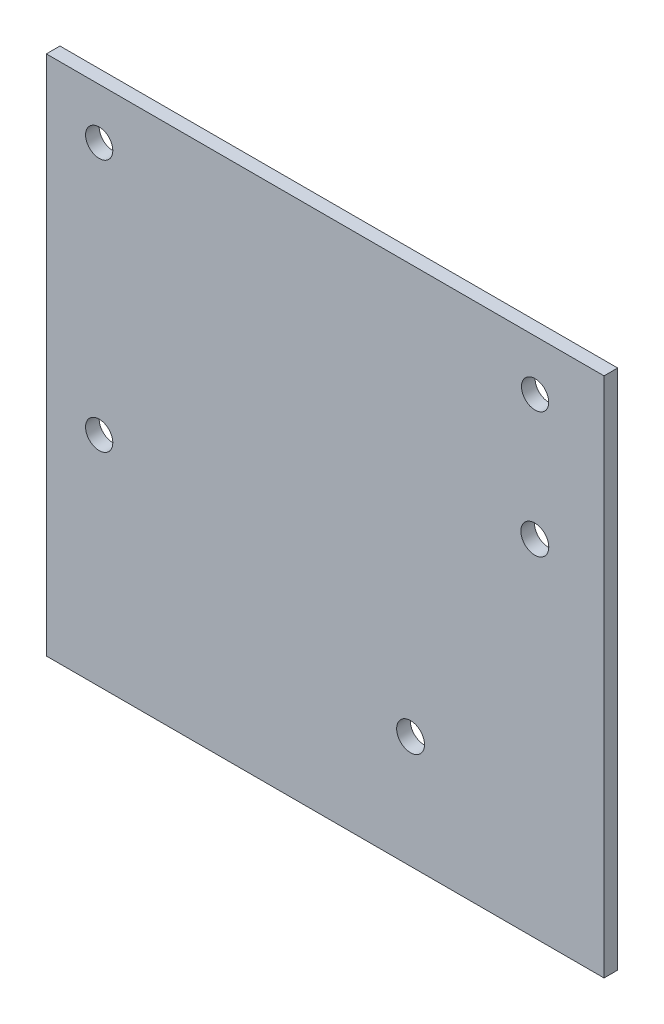
SolidWorks part; units mm, degrees
ref_plane "Front Plane" through (0, 0, 0) normal (0, 0, 1) x (1, 0, 0)
ref_plane "Top Plane" through (0, 0, 0) normal (0, 1, 0) x (1, 0, 0)
ref_plane "Right Plane" through (0, 0, 0) normal (1, 0, 0) x (0, 0, -1)
sketch "Sketch1" plane through (0, 0, 0) normal (0, 0, 1) x (1, 0, 0)
  line L0 (59.8766, 278.2835) -> (9.0766, 278.2835) construction
  line L1 (-37.716, 306.5959) -> (92.264, 306.5959)
  line L2 (-37.716, 306.5959) -> (-37.716, 185.0571)
  line L3 (-37.716, 185.0571) -> (92.264, 185.0571)
  line L4 (92.264, 306.5959) -> (92.264, 185.0571)
  line L5 (59.8766, 227.4835) -> (59.8766, 278.2835) construction
  line L6 (9.0766, 227.4835) -> (59.8766, 227.4835) construction
  circle A0 centre (-25.4, 235.8571) radius 3.175
  circle A1 centre (-25.4, 294.8214) radius 3.175
  circle A3 centre (76.2, 294.8214) radius 3.175
  circle A4 centre (76.1326, 265.5835) radius 3.2512
  circle A5 centre (47.1766, 211.2275) radius 3.2512
  dimension "D2" = 6.35
  dimension "D3" = 6.35
  dimension "D6" = 6.35
  dimension "D9" = 6.5024
  dimension "D12" = 6.5024
  dimension "D4" = 12.316
  dimension "D5" = 50.8
  dimension "D1" = 11.7745
  dimension "D7" = 12.7
  dimension "D8" = 16.256
  dimension "D10" = 16.256
  dimension "D11" = 12.7
extrude "Boss-Extrude1" add sketch "Sketch1" along normal blind 3.175
equation "\"80/20 to Center Hole\"= .64in"
equation "\"D8@Sketch1\"=\"80/20 to Center Hole\""
equation "\"D10@Sketch1\"=\"80/20 to Center Hole\""
equation "\"80/20 from Edge\"= 0.5in"
equation "\"D11@Sketch1\"=\"80/20 from Edge\""
equation "\"D7@Sketch1\"=\"80/20 from Edge\""
